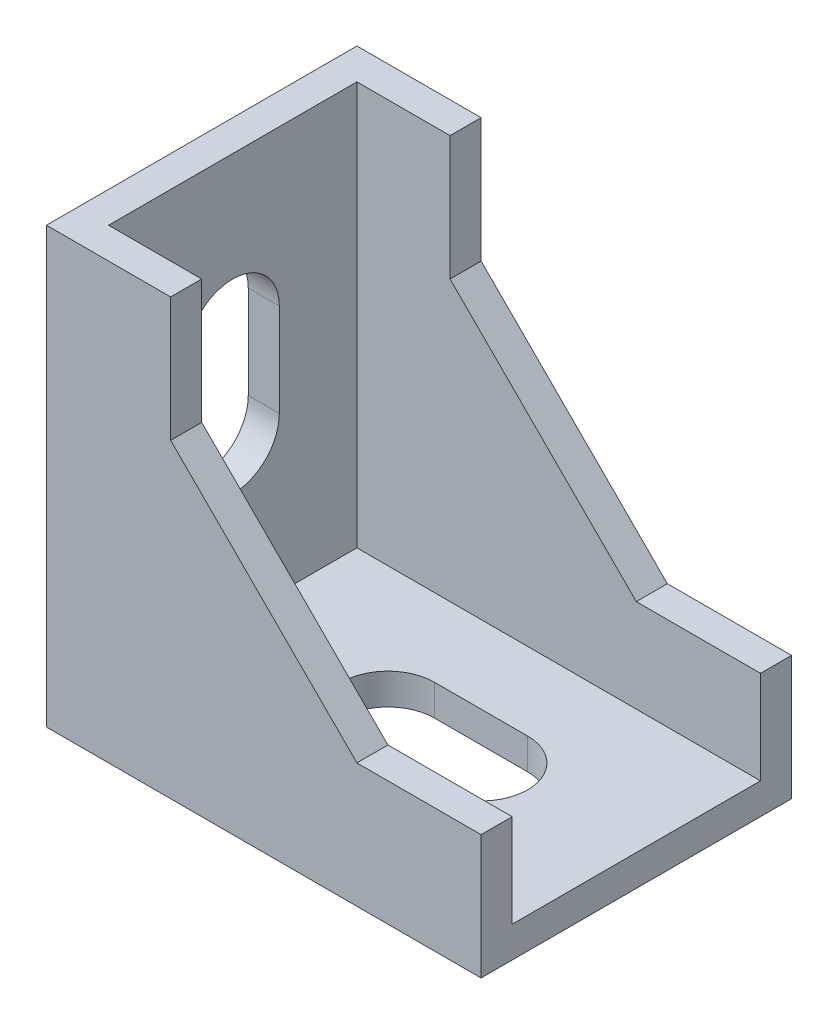
SolidWorks part; units mm, degrees
ref_plane "Front Plane" through (0, 0, 0) normal (0, 0, 1) x (1, 0, 0)
ref_plane "Top Plane" through (0, 0, 0) normal (0, 1, 0) x (1, 0, 0)
ref_plane "Right Plane" through (0, 0, 0) normal (1, 0, 0) x (0, 0, -1)
sketch "Sketch1" plane through (0, 0, 0) normal (0, 0, 1) x (1, 0, 0)
  line L0 (0, 0) -> (0, 28)
  line L1 (0, 0) -> (28, 0)
  line L2 (0, 28) -> (8, 28)
  line L3 (8, 28) -> (8, 20)
  line L4 (8, 20) -> (20, 8)
  line L5 (20, 8) -> (28, 8)
  line L6 (28, 8) -> (28, 0)
  dimension "D1" = 28
  dimension "D2" = 8
  dimension "D3" = 8
extrude "Boss-Extrude1" add sketch "Sketch1" along normal blind 20
sketch "Sketch2" plane through (28, 0, 0) normal (1, 0, 0) x (0, 0, -1)
  line L0 (-20, 0) -> (-20, 8) construction
  line L1 (-20, 0) -> (-20, 8)
  line L2 (0, 0) -> (0, 8) construction
  line L3 (-18, 28) -> (-2, 28)
  line L4 (-18, 28) -> (-18, 2)
  line L5 (-18, 2) -> (-2, 2)
  line L6 (-2, 28) -> (-2, 2)
  line L7 (-20, 28) -> (0, 28) construction
  line L8 (-20, 0) -> (0, 0) construction
  line M2 (0, 8) -> (-20, 8)
  dimension "D1" = 2
  dimension "D2" = 2
  dimension "D3" = 0
  dimension "D4" = 2
ref_plane "Plane1" through (2, 0, 0) normal (-1, 0, 0) x (0, 0, 1)
extrude "Cut-Extrude1" cut sketch "Sketch2" against normal up to surface (26 mm away) contours L6 L3 L4 M2 | L6 L4 L5 M2
sketch "Sketch3" plane through (2, 0, 0) normal (1, 0, 0) x (0, 0, -1)
  line L0 (-10, 28) -> (-10, 2) construction
  line L1 (-18, 15) -> (-2, 15) construction
  line L2 (-13, 18) -> (-13, 12)
  line L3 (-7, 18) -> (-7, 12)
  line L4 (-2, 28) -> (-18, 28)
  line L5 (-18, 28) -> (-18, 2)
  line L6 (-18, 2) -> (-2, 2)
  line L7 (-2, 2) -> (-2, 28)
  line L8 (-2, 28) -> (-18, 28)
  line L9 (-18, 28) -> (-18, 2)
  line L10 (-18, 2) -> (-2, 2)
  line L11 (-2, 2) -> (-2, 28)
  circle A0 centre (-10, 18) radius 3
  circle A1 centre (-10, 12) radius 3
  dimension "D3" = 6
  dimension "D2" = 3
  dimension "D1" = 0
extrude "Cut-Extrude2" cut sketch "Sketch3" against normal up to surface (2 mm away) contours A0 | L2 A1 A0 | A0 A1 L3 | A1 up to face at (0, 14, 10)
ref_plane "Plane2" through (0, 0, 0) normal (0.7071, -0.7071, 0) x (0, 0, -1)
mirror "Mirror2" about plane through (0, 0, 0) normal (0.7071, -0.7071, 0) of "Cut-Extrude2"
sketch "Sketch4" plane through (0, 0, 0) normal (-1, 0, 0) x (0, 0, 1)
  line L0 (7, 18) -> (7, 12) construction
  line L1 (13, 18) -> (13, 12) construction
  line L2 (7, 18) -> (7, 12)
  line L3 (13, 18) -> (13, 12)
  line L4 (0, 28) -> (0, 0)
  line L5 (0, 0) -> (20, 0)
  line L6 (20, 0) -> (20, 28)
  line L7 (20, 28) -> (0, 28)
  line L8 (0, 28) -> (0, 0)
  line L9 (0, 0) -> (20, 0)
  line L10 (20, 0) -> (20, 28)
  line L11 (20, 28) -> (0, 28)
  line L12 (18, 28) -> (2, 28)
  line L13 (18, 2) -> (18, 28)
  line L14 (2, 2) -> (18, 2)
  line L15 (2, 28) -> (2, 2)
  line L16 (18, 28) -> (2, 28)
  line L17 (18, 2) -> (18, 28)
  line L18 (2, 2) -> (18, 2)
  line L19 (2, 28) -> (2, 2)
  circle A1 centre (10, 12) radius 3
  circle A2 centre (10, 12) radius 3
  circle A3 centre (10, 18) radius 3
  circle A4 centre (10, 18) radius 3
  dimension "D1" = 0
  dimension "D2" = 0
  dimension "D3" = 0
  dimension "D4" = 0
sketch "Sketch5" plane through (0, 2, 0) normal (0, 1, 0) x (1, 0, 0)
  circle A0 centre (12, -10) radius 3
